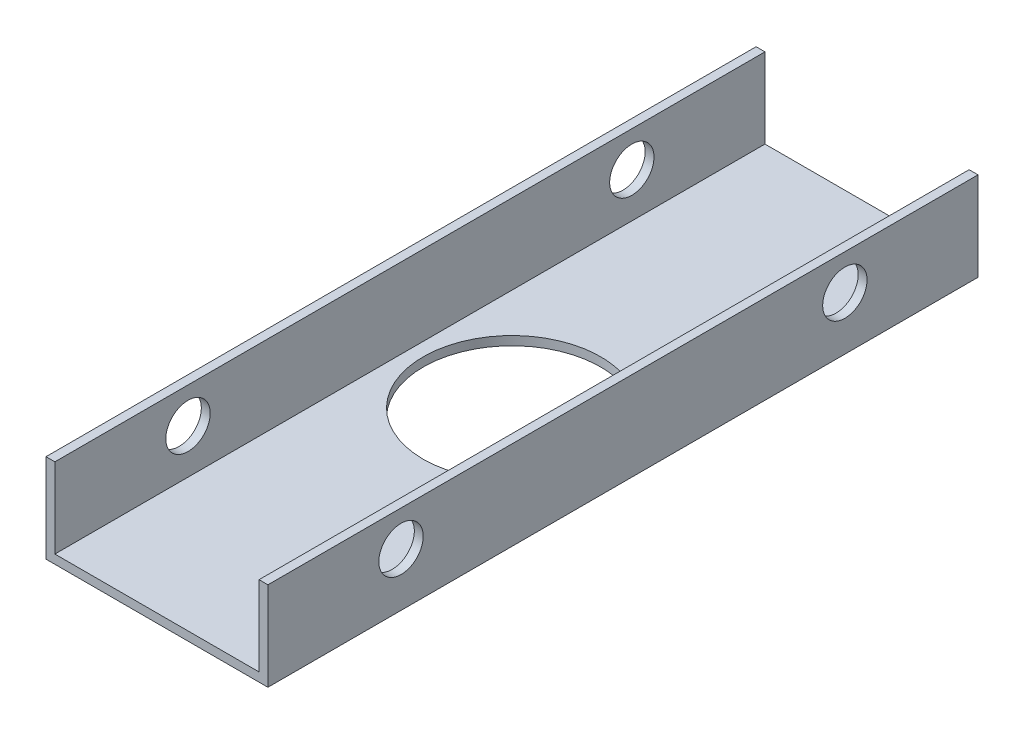
SolidWorks part; units mm, degrees
ref_plane "Front Plane" through (0, 0, 0) normal (0, 0, 1) x (1, 0, 0)
ref_plane "Top Plane" through (0, 0, 0) normal (0, 1, 0) x (1, 0, 0)
ref_plane "Right Plane" through (0, 0, 0) normal (1, 0, 0) x (0, 0, -1)
sketch "Sketch2" plane through (0, 0, 0) normal (0, 1, 0) x (1, 0, 0)
  line L1 (-11.5, -40) -> (11.5, -40)
  line L2 (-11.5, -40) -> (-11.5, 40)
  line L3 (-11.5, 40) -> (11.5, 40)
  line L4 (11.5, -40) -> (11.5, 40)
  circle A0 centre (0, 0) radius 10
  dimension "D1" = 20
  dimension "D2" = 23
  dimension "D3" = 80
  dimension "D4" = 11.5
  dimension "D5" = 11.5
  dimension "D6" = 40
extrude "Boss-Extrude1" add sketch "Sketch2" along normal blind 1
sketch "Sketch3" plane through (-11.5, 0, 0) normal (-1, 0, 0) x (0, 0, 1)
  line L0 (-40, 0) -> (-40, 10)
  line L1 (-40, 10) -> (40, 10)
  line L2 (40, 10) -> (40, 0)
  line L3 (40, 0) -> (-40, 0)
  line L4 (-40, 1) -> (40, 1) construction
  line L5 (0, -5.5) -> (0, 5.5) construction
  circle A0 centre (-25, 6) radius 2.5
  circle A1 centre (25, 6) radius 2.5
  dimension "D3" = 5
  dimension "D1" = 10
  dimension "D2" = 5
  dimension "D4" = 15
extrude "Boss-Extrude2" add sketch "Sketch3" along normal blind 1
mirror "Mirror1" about plane through (0, 0, 0) normal (1, 0, 0) of "Boss-Extrude2"
